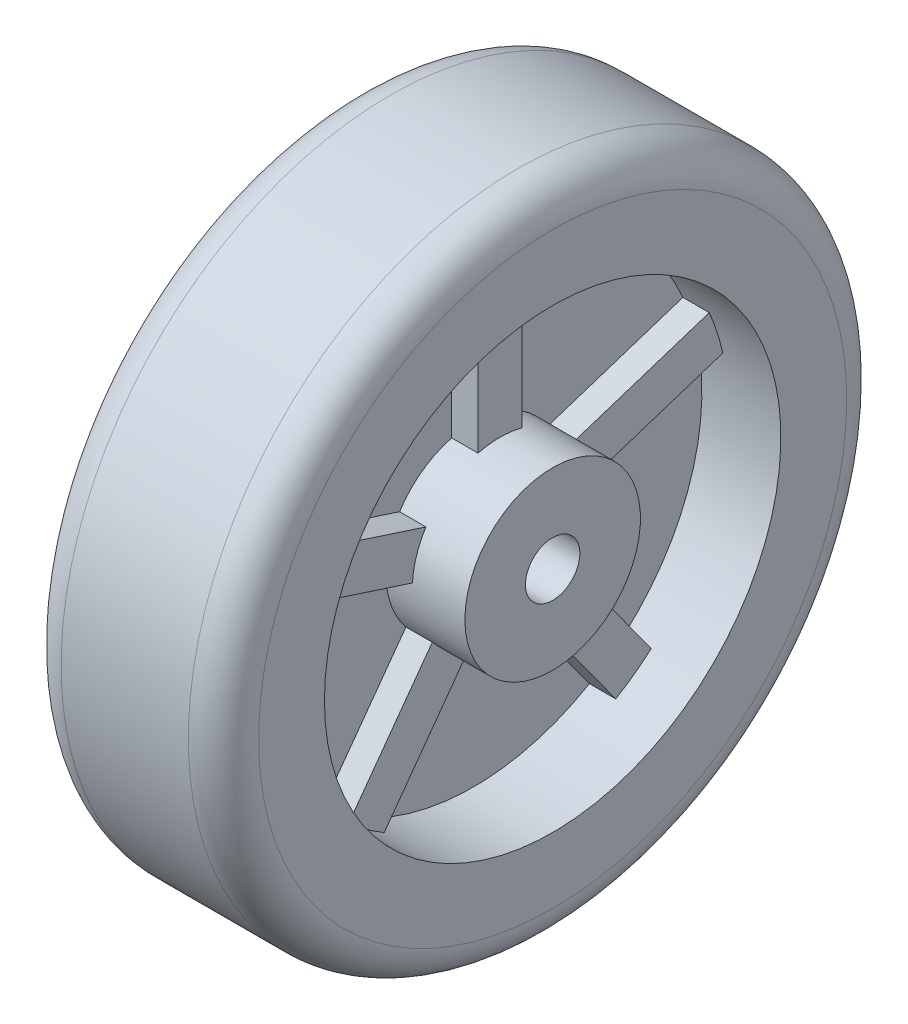
SolidWorks part; units mm, degrees
ref_plane "前视基准面" through (0, 0, 0) normal (0, 0, 1) x (1, 0, 0)
ref_plane "上视基准面" through (0, 0, 0) normal (0, 1, 0) x (1, 0, 0)
ref_plane "右视基准面" through (0, 0, 0) normal (1, 0, 0) x (0, 0, -1)
sketch "草图1" plane through (0, 0, 0) normal (1, 0, 0) x (0, 0, -1)
  circle A0 centre (0, 0) radius 60
  dimension "D1" = 120
extrude "凸台-拉伸1" add sketch "草图1" along normal mid plane 45
sketch "草图2" plane through (22.5, 0, 0) normal (1, 0, 0) x (0, 0, -1)
  circle A0 centre (0, 0) radius 60
  circle A1 centre (0, 0) radius 75
  dimension "D1" = 150
extrude "凸台-拉伸2" add sketch "草图2" against normal blind 45 separate body
fillet "圆角1" radius 8 2 edges at (-22.5, 0, -75) (22.5, 0, -75)
sketch "草图3" plane through (-22.5, 0, 0) normal (-1, 0, 0) x (0, 0, 1)
  circle A0 centre (0, 0) radius 52
  circle A2 centre (0, 0) radius 20
  dimension "D1" = 104
  dimension "D3" = 40
extrude "切除-拉伸1" cut sketch "草图3" against normal blind 18
sketch "草图4" plane through (-22.5, 0, 0) normal (-1, 0, 0) x (0, 0, 1)
  circle A0 centre (0, 0) radius 6.2
  dimension "D1" = 12.4
extrude "切除-拉伸2" cut sketch "草图4" against normal through all
sketch "草图5" plane through (-4.5, 0, 0) normal (-1, 0, 0) x (0, 0, 1)
  line L0 (-5, 51.7591) -> (-5, 19.3649)
  line L1 (5, 51.7591) -> (5, 19.3649)
  circle A0 centre (0, 0) radius 52 construction
  circle A1 centre (0, 0) radius 20 construction
  circle A2 centre (0, 0) radius 52 construction
  circle A3 centre (0, 0) radius 20 construction
  arc A4 (5, 51.7591) -> (-5, 51.7591) centre (0, 0) ccw
  arc A5 (5, 19.3649) -> (-5, 19.3649) centre (0, 0) ccw
  circle M1 centre (0, 0) radius 20
  circle M2 centre (0, 0) radius 52
  dimension "D1" = 10
  dimension "D2" = 5
extrude "凸台-拉伸3" add sketch "草图5" along normal blind 6 contours L1 L0 M2 M1
pattern_circular "阵列(圆周)1" count 5 over 360 about axis through (0, 0, 0) along (1, 0, 0) of "凸台-拉伸3"
mirror "镜向2" about plane through (0, 0, 0) normal (1, 0, 0) of "切除-拉伸1", "凸台-拉伸3", "阵列(圆周)1"
